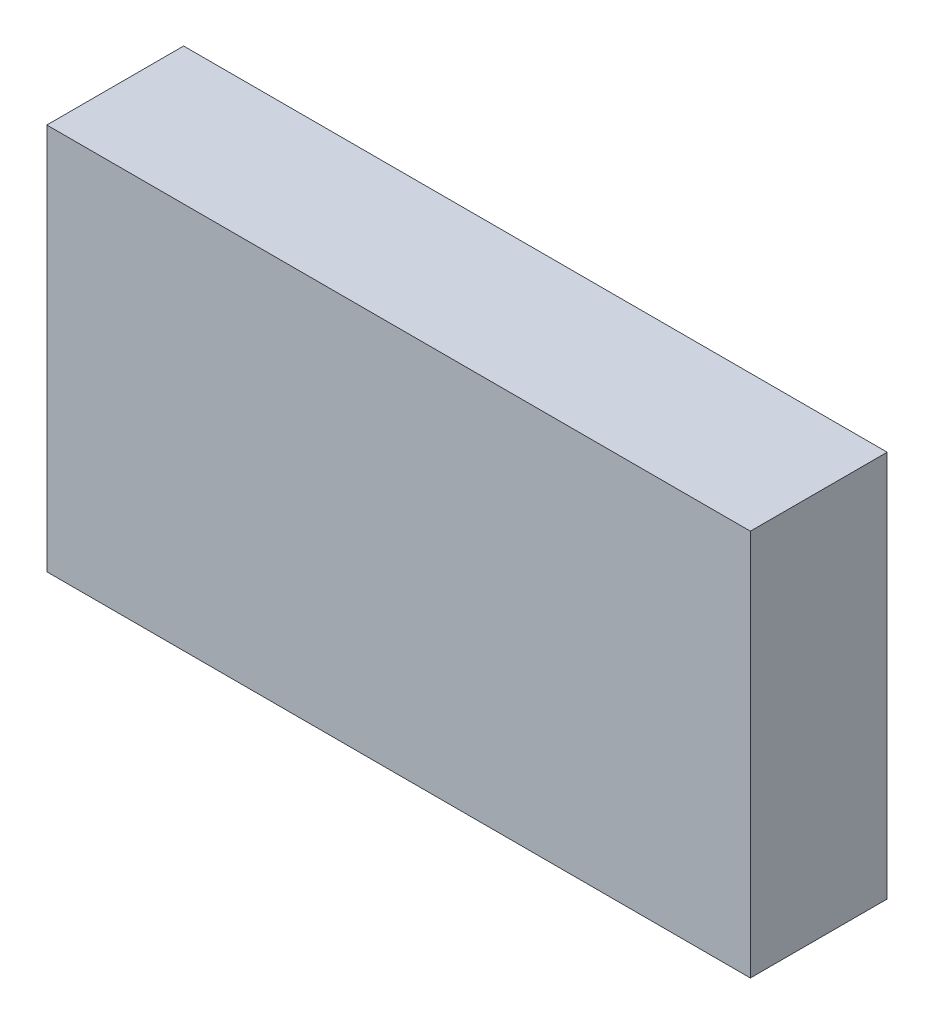
SolidWorks part; units mm, degrees
ref_plane "Front Plane" through (0, 0, 0) normal (0, 0, 1) x (1, 0, 0)
ref_plane "Top Plane" through (0, 0, 0) normal (0, 1, 0) x (1, 0, 0)
ref_plane "Right Plane" through (0, 0, 0) normal (1, 0, 0) x (0, 0, -1)
sketch "Sketch1" plane through (0, 0, 0) normal (0, 0, 1) x (1, 0, 0)
  line L1 (0, 0) -> (36, 0)
  line L2 (0, 0) -> (0, 19.8)
  line L3 (0, 19.8) -> (36, 19.8)
  line L4 (36, 0) -> (36, 19.8)
  dimension "D1" = 36
  dimension "D2" = 19.8
extrude "Boss-Extrude1" add sketch "Sketch1" along normal blind 7
